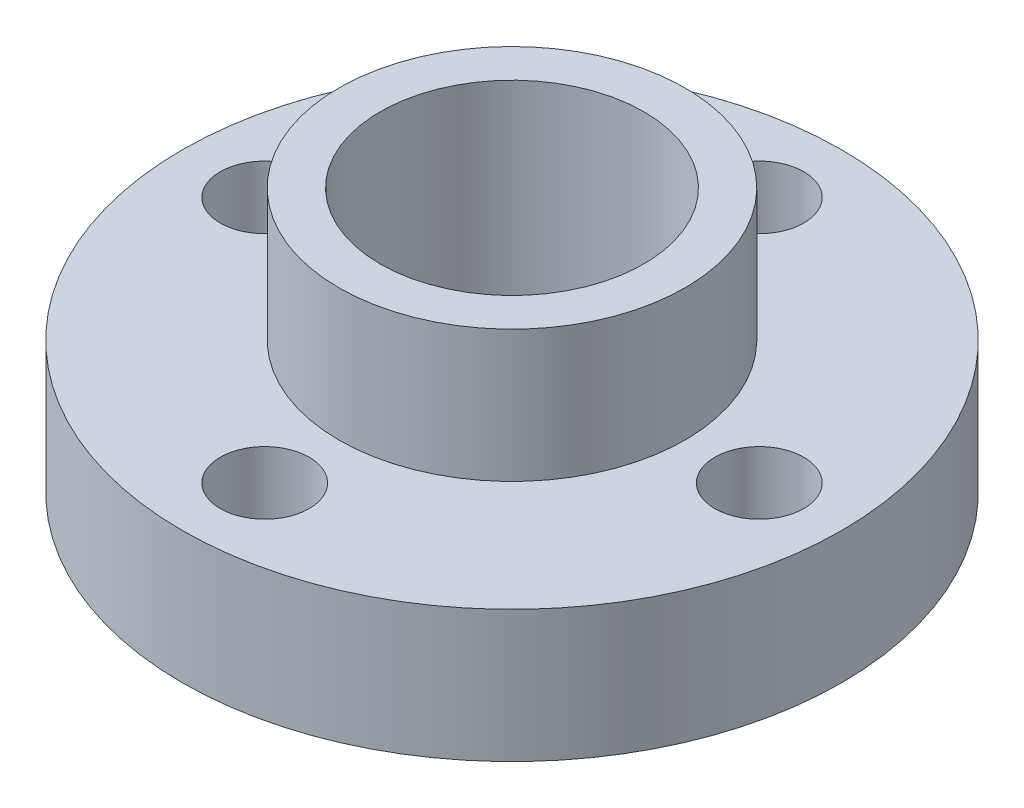
SolidWorks part; units mm, degrees
ref_plane "Front Plane" through (0, 0, 0) normal (0, 0, 1) x (1, 0, 0)
ref_plane "Top Plane" through (0, 0, 0) normal (0, 1, 0) x (1, 0, 0)
ref_plane "Right Plane" through (0, 0, 0) normal (1, 0, 0) x (0, 0, -1)
sketch "Sketch1" plane through (0, 0, 0) normal (0, 1, 0) x (1, 0, 0)
  circle A0 centre (0, 0) radius 10
  dimension "D1" = 20
extrude "Boss-Extrude1" add sketch "Sketch1" along normal blind 4
sketch "Sketch2" plane through (0, 4, 0) normal (0, 1, 0) x (1, 0, 0)
  circle A0 centre (0, 0) radius 5.25
  dimension "D1" = 10.5
extrude "Boss-Extrude2" add sketch "Sketch2" along normal blind 4
sketch "Sketch3" plane through (0, 4, 0) normal (0, 1, 0) x (1, 0, 0)
  line L0 (0, 0) -> (0, 7.5) construction
  line L1 (0, 0) -> (7.5, 0) construction
  circle A0 centre (0, 7.5) radius 1.35
  circle A1 centre (7.5, 0) radius 1.35
  circle A2 centre (0, -7.5) radius 1.35
  circle A3 centre (-7.5, 0) radius 1.35
  dimension "D3" = 7.5
  dimension "D4" = 2.7
  dimension "D1" = 7.5
extrude "Cut-Extrude1" cut sketch "Sketch3" against normal through all
sketch "Sketch4" plane through (0, 8, 0) normal (0, 1, 0) x (-1, 0, 0)
  circle A0 centre (0, 0) radius 4
  dimension "D1" = 8
extrude "Cut-Extrude2" cut sketch "Sketch4" against normal through all
